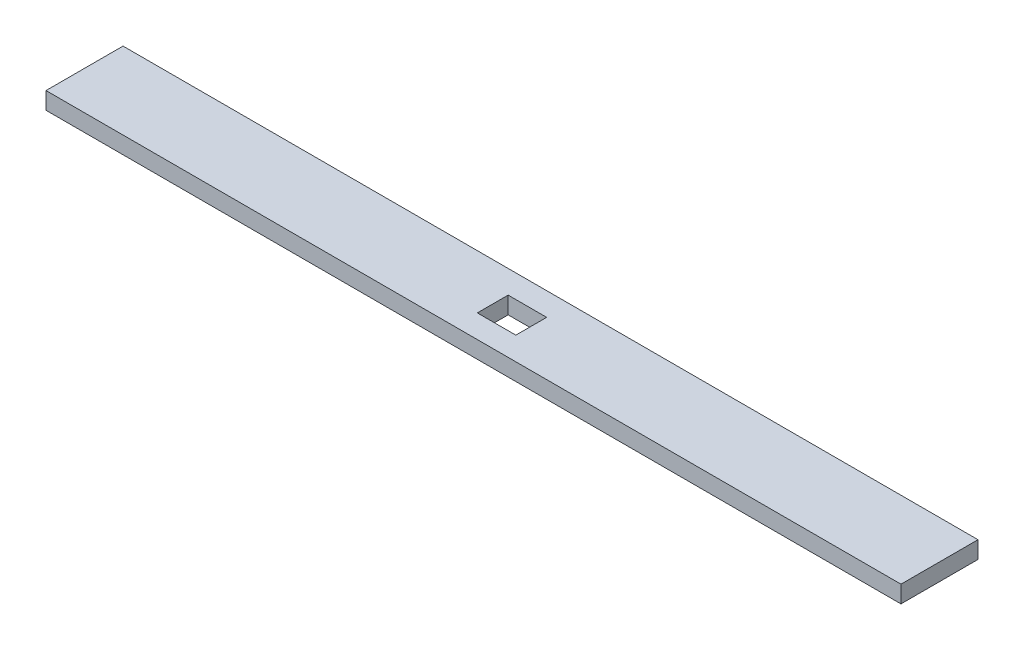
SolidWorks part; units mm, degrees
ref_plane "Front Plane" through (0, 0, 0) normal (0, 0, 1) x (1, 0, 0)
ref_plane "Top Plane" through (0, 0, 0) normal (0, 1, 0) x (1, 0, 0)
ref_plane "Right Plane" through (0, 0, 0) normal (1, 0, 0) x (0, 0, -1)
sketch "Sketch1" plane through (0, 0, 0) normal (1, 0, 0) x (0, 0, -1)
  line L1 (0, 0) -> (45, 0)
  line L2 (0, 0) -> (0, 10)
  line L3 (0, 10) -> (45, 10)
  line L4 (45, 0) -> (45, 10)
  dimension "D1" = 45
  dimension "D2" = 10
extrude "Boss-Extrude1" add sketch "Sketch1" along normal blind 499.5
ref_plane "Plane1" through (0, 0, -22.5) normal (0, 0, 1) x (1, 0, 0)
ref_plane "Plane2" through (249.75, 0, 0) normal (-1, 0, 0) x (0, 0, 1)
sketch "Sketch2" plane through (0, 10, 0) normal (0, 1, 0) x (1, 0, 0)
  line L0 (499.5, 22.5) -> (479.9185, 22.5) construction
  line L1 (261, 13.5) -> (238.5, 13.5)
  line L2 (261, 13.5) -> (261, 31.5)
  line L3 (261, 31.5) -> (238.5, 31.5)
  line L4 (238.5, 13.5) -> (238.5, 31.5)
  line L5 (499.5, 45) -> (499.5, 0) construction
  line L6 (499.5, 0) -> (0, 0) construction
  point P8 (249.75, 13.5)
  point P11 (249.75, 0)
  dimension "D1" = 18
  dimension "D2" = 22.5
extrude "Cut-Extrude1" cut sketch "Sketch2" against normal through all
pattern_linear "LPattern1" [suppressed] count 2 spacing 120
